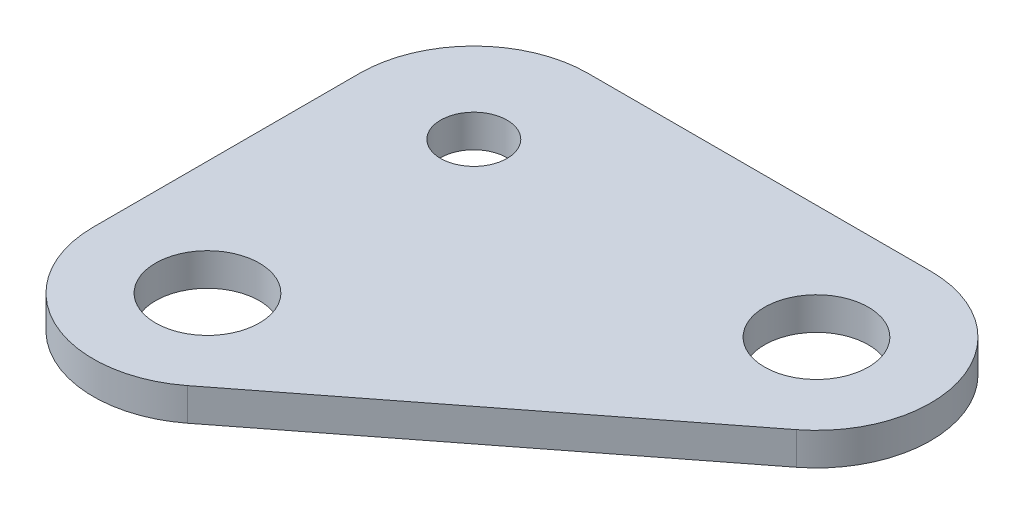
SolidWorks part; units mm, degrees
ref_plane "Front" through (0, 0, 0) normal (0, 0, 1) x (1, 0, 0)
ref_plane "Top" through (0, 0, 0) normal (0, 1, 0) x (1, 0, 0)
ref_plane "Right" through (0, 0, 0) normal (1, 0, 0) x (0, 0, -1)
sketch "Sketch2" plane through (0, 0, 0) normal (0, 1, 0) x (1, 0, 0)
  line L0 (0, 0) -> (0, 12.825) construction
  line L1 (0, 12.825) -> (16.5, 12.825) construction
  line L2 (-5.5, -11.241) -> (32.5382, 18.325) construction
  line L3 (32.5382, 18.325) -> (-5.5, 18.325) construction
  line L4 (-5.5, 18.325) -> (-5.5, -11.241) construction
  line L5 (-5.5, 0) -> (-5.5, 12.825)
  line L6 (0, 18.325) -> (16.5, 18.325)
  line L7 (19.8753, 8.4825) -> (3.3753, -4.3425)
  circle A0 centre (0, 12.825) radius 1.6
  circle A1 centre (16.5, 12.825) radius 2.5
  circle A2 centre (0, 0) radius 2.5
  circle A3 centre (16.5, 12.825) radius 5.5 construction
  circle A4 centre (0, 12.825) radius 5.5 construction
  circle A5 centre (0, 0) radius 5.5 construction
  arc A6 (-5.5, 12.825) -> (0, 18.325) centre (0, 12.825) cw
  arc A7 (16.5, 18.325) -> (19.8753, 8.4825) centre (16.5, 12.825) cw
  arc A8 (3.3753, -4.3425) -> (-5.5, 0) centre (0, 0) cw
  dimension "D3" = 5
  dimension "D4" = 3.2
  dimension "D5" = 3
  dimension "D1" = 12.825
  dimension "D2" = 16.5
extrude "Boss-Extrude1" add sketch "Sketch2" along normal blind 1.57
other "Move Face1" [suppressed] parameters "D1"=0.0762
